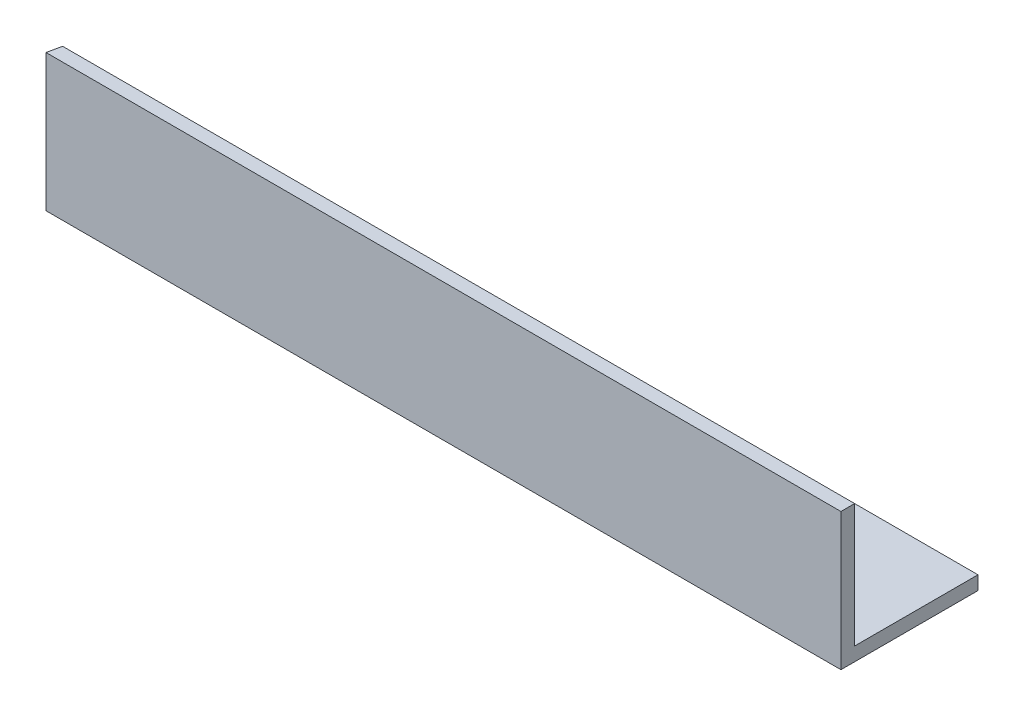
SolidWorks part; units mm, degrees
ref_plane "Front Plane" through (0, 0, 0) normal (0, 0, 1) x (1, 0, 0)
ref_plane "Top Plane" through (0, 0, 0) normal (0, 1, 0) x (1, 0, 0)
ref_plane "Right Plane" through (0, 0, 0) normal (1, 0, 0) x (0, 0, -1)
sketch "Sketch1" plane through (0, 0, 0) normal (1, 0, 0) x (0, 0, -1)
  line L0 (0, 20) -> (0, 0)
  line L1 (0, 0) -> (20, 0)
  line L2 (20, 0) -> (20, 2)
  line L3 (20, 2) -> (2, 2)
  line L4 (2, 2) -> (2, 20)
  line L5 (0, 20) -> (2, 20)
  dimension "D1" = 20
  dimension "D2" = 20
  dimension "D3" = 2
  dimension "D4" = 2
extrude "Boss-Extrude1" add sketch "Sketch1" along normal blind 116
sketch "Sketch2" plane through (0, 0, 0) normal (0, -1, 0) x (1, 0, 0)
  line L0 (0, 0) -> (4.2511, -20)
  line L1 (116, -20) -> (0, -20) construction
  line L2 (4.2511, -20) -> (0, -20)
  line L3 (0, -20) -> (0, 0)
  dimension "D1" = 12
extrude "Cut-Extrude1" cut sketch "Sketch2" against normal through all
